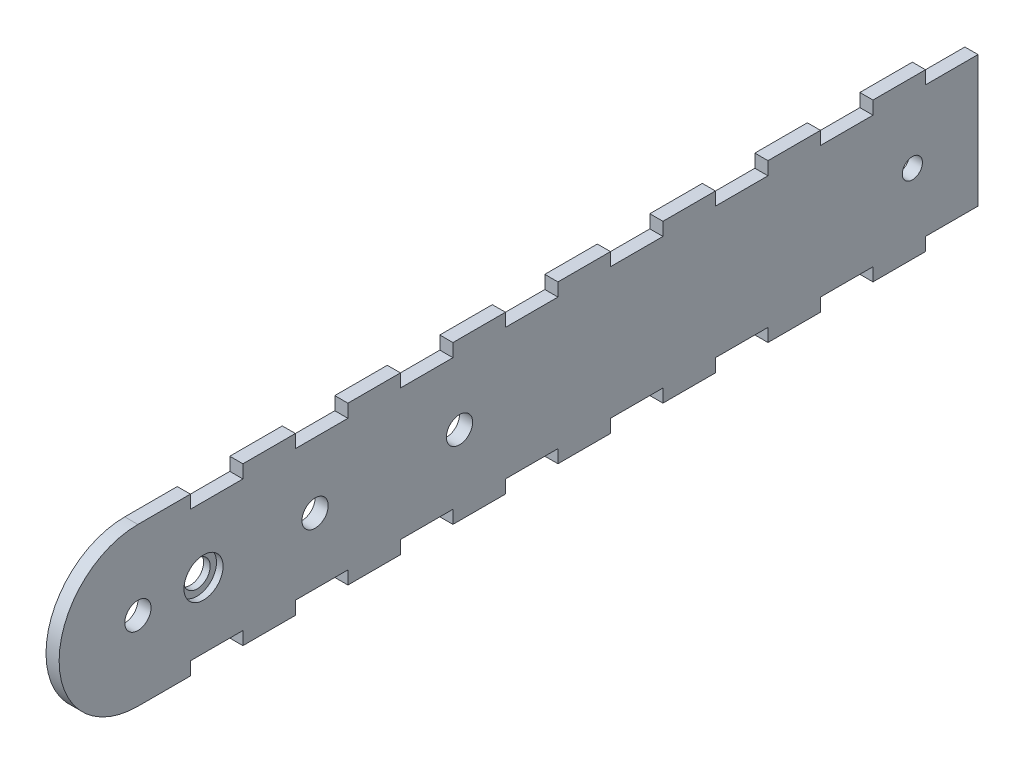
SolidWorks part; units mm, degrees
material "Acrylic (Medium-high impact)"
ref_plane "Front Plane" through (0, 0, 0) normal (0, 0, 1) x (1, 0, 0)
ref_plane "Top Plane" through (0, 0, 0) normal (0, 1, 0) x (1, 0, 0)
ref_plane "Right Plane" through (0, 0, 0) normal (1, 0, 0) x (0, 0, -1)
sketch "Sketch1" plane through (0, 0, 0) normal (1, 0, 0) x (0, 0, -1)
  line L0 (0, 19.05) -> (203.2, 19.05)
  line L1 (0, -19.05) -> (203.2, -19.05)
  line L2 (203.2, -19.05) -> (203.2, 19.05)
  line L3 (203.2, 0) -> (7.9375, 0) construction
  line L4 (203.2, 19.05) -> (190.5, 19.05)
  line L5 (203.2, 19.05) -> (203.2, 15.875)
  line L6 (203.2, 15.875) -> (190.5, 15.875)
  line L7 (190.5, 19.05) -> (190.5, 15.875)
  line L8 (190.5, -19.05) -> (190.5, -15.875)
  line L9 (203.2, -15.875) -> (190.5, -15.875)
  line L10 (203.2, -19.05) -> (203.2, -15.875)
  line L11 (165.1, 19.05) -> (165.1, 15.875)
  line L12 (165.1, -19.05) -> (165.1, -15.875)
  line L13 (177.8, -15.875) -> (165.1, -15.875)
  line L14 (177.8, 15.875) -> (165.1, 15.875)
  line L15 (177.8, 19.05) -> (177.8, 15.875)
  line L16 (177.8, -19.05) -> (177.8, -15.875)
  line L17 (139.7, 19.05) -> (139.7, 15.875)
  line L18 (139.7, -19.05) -> (139.7, -15.875)
  line L19 (152.4, -15.875) -> (139.7, -15.875)
  line L20 (152.4, 15.875) -> (139.7, 15.875)
  line L21 (152.4, 19.05) -> (152.4, 15.875)
  line L22 (152.4, -19.05) -> (152.4, -15.875)
  line L23 (114.3, 19.05) -> (114.3, 15.875)
  line L24 (114.3, -19.05) -> (114.3, -15.875)
  line L25 (127, -15.875) -> (114.3, -15.875)
  line L26 (127, 15.875) -> (114.3, 15.875)
  line L27 (127, 19.05) -> (127, 15.875)
  line L28 (127, -19.05) -> (127, -15.875)
  line L29 (88.9, 19.05) -> (88.9, 15.875)
  line L30 (88.9, -19.05) -> (88.9, -15.875)
  line L31 (101.6, -15.875) -> (88.9, -15.875)
  line L32 (101.6, 15.875) -> (88.9, 15.875)
  line L33 (101.6, 19.05) -> (101.6, 15.875)
  line L34 (101.6, -19.05) -> (101.6, -15.875)
  line L35 (63.5, 19.05) -> (63.5, 15.875)
  line L36 (63.5, -19.05) -> (63.5, -15.875)
  line L37 (76.2, -15.875) -> (63.5, -15.875)
  line L38 (76.2, 15.875) -> (63.5, 15.875)
  line L39 (76.2, 19.05) -> (76.2, 15.875)
  line L40 (76.2, -19.05) -> (76.2, -15.875)
  line L41 (38.1, 19.05) -> (38.1, 15.875)
  line L42 (38.1, -19.05) -> (38.1, -15.875)
  line L43 (50.8, -15.875) -> (38.1, -15.875)
  line L44 (50.8, 15.875) -> (38.1, 15.875)
  line L45 (50.8, 19.05) -> (50.8, 15.875)
  line L46 (50.8, -19.05) -> (50.8, -15.875)
  line L47 (12.7, 19.05) -> (12.7, 15.875)
  line L48 (12.7, -19.05) -> (12.7, -15.875)
  line L49 (25.4, -15.875) -> (12.7, -15.875)
  line L50 (25.4, 15.875) -> (12.7, 15.875)
  line L51 (25.4, 19.05) -> (25.4, 15.875)
  line L52 (25.4, -19.05) -> (25.4, -15.875)
  circle A0 centre (0, 0) radius 3.175
  arc A1 (0, 19.05) -> (0, -19.05) centre (0, 0) ccw
  dimension "D1" = 6.35
  dimension "D2" = 38.1
  dimension "D3" = 203.2
  dimension "D4" = 3.175
  dimension "D5" = 12.7
  dimension "D7" = 12.7
  dimension "D8" = 195.2625
  dimension "D6" = 8
extrude "Boss-Extrude1" add sketch "Sketch1" along normal blind 3.175
sketch "Sketch2" plane through (3.175, 0, 0) normal (1, 0, 0) x (0, 0, -1)
  line L0 (15.875, 0) -> (0, 0) construction
  line L1 (203.2, 0) -> (187.325, 0) construction
  line L2 (203.2, -15.875) -> (203.2, 15.875) construction
  line L4 (77.7875, 0) -> (42.8625, 0) construction
  circle A0 centre (0, 0) radius 7.9375 construction
  circle A1 centre (15.875, 0) radius 7.9375 construction
  circle A2 centre (15.875, 0) radius 3.2004
  circle A5 centre (187.325, 0) radius 2.4384
  circle A6 centre (42.8625, 0) radius 3.175
  circle A7 centre (77.7875, 0) radius 3.175
  point P20 (60.325, 0)
  dimension "D1" = 15.875
  dimension "D2" = 6.4008
  dimension "D4" = 4.8768
  dimension "D5" = 6.35
  dimension "D3" = 15.875
  dimension "D6" = 34.925
  dimension "D7" = 127
  dimension "D8" = 44.45
extrude "Cut-Extrude2" cut sketch "Sketch2" against normal through all
sketch "Sketch3" plane through (3.175, 0, 0) normal (1, 0, 0) x (0, 0, -1)
  circle A1 centre (15.875, 0) radius 4.7307
  circle A2 centre (15.875, 0) radius 3.2004 construction
  dimension "D2" = 9.4615
extrude "Cut-Extrude3" cut sketch "Sketch3" against normal blind 1.5875
